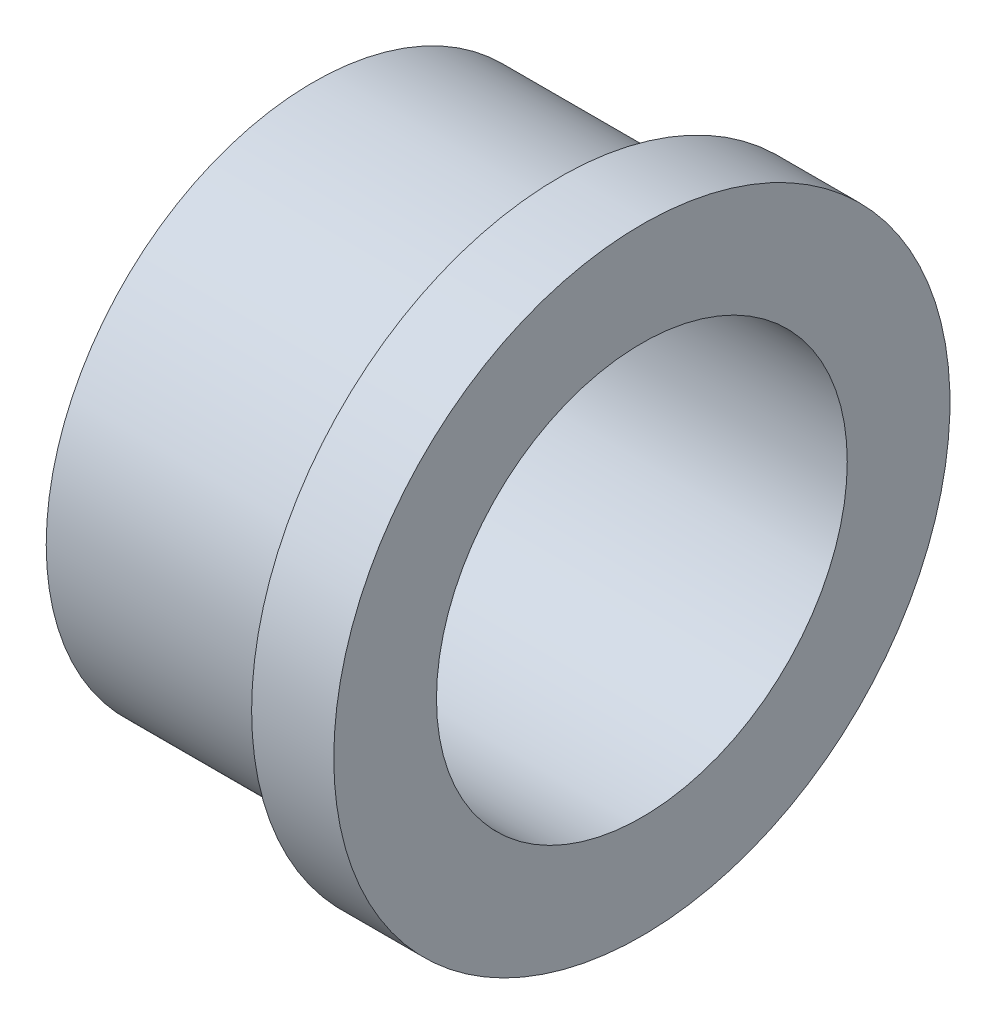
SolidWorks part; units mm, degrees
ref_plane "前视基准面" through (0, 0, 0) normal (0, 0, 1) x (1, 0, 0)
ref_plane "上视基准面" through (0, 0, 0) normal (0, 1, 0) x (1, 0, 0)
ref_plane "右视基准面" through (0, 0, 0) normal (1, 0, 0) x (0, 0, -1)
other "Configuration Table"
sketch "草图1" plane through (0, 0, 0) normal (0, 0, 1) x (1, 0, 0)
  line L0 (-5, 0) -> (21, 0) construction
  line L1 (0, 10) -> (0, 13)
  line L2 (0, 13) -> (12, 13)
  line L3 (12, 13) -> (12, 15)
  line L4 (12, 15) -> (16, 15)
  line L5 (16, 15) -> (16, 10)
  line L6 (16, 10) -> (0, 10)
revolve "01_GLAND" add sketch "草图1" angle 360 about L0
